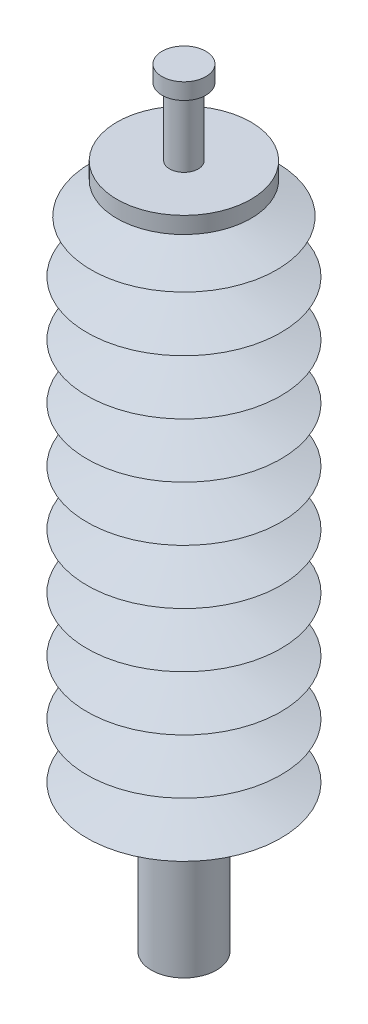
SolidWorks part; units mm, degrees
ref_plane "Alzado" through (0, 0, 0) normal (0, 0, 1) x (1, 0, 0)
ref_plane "Planta" through (0, 0, 0) normal (0, 1, 0) x (1, 0, 0)
ref_plane "Vista lateral" through (0, 0, 0) normal (1, 0, 0) x (0, 0, -1)
sketch "Croquis1" plane through (0, 0, 0) normal (0, 0, 1) x (1, 0, 0)
  line L0 (0, 0) -> (0, 1000)
  line L1 (0, 1000) -> (0, 1050.9393)
  line L2 (21.9878, 1050.9393) -> (102.821, 1050.9393)
  line L3 (102.821, 1050.9393) -> (102.821, 1025.4697)
  line L4 (102.821, 1025.4697) -> (50, 1025.4697)
  line L5 (50, 1025.4697) -> (50, 1000)
  line L6 (50, 1000) -> (142.4367, 976.99)
  line L7 (142.4367, 976.99) -> (50, 921.4009)
  line L8 (50, 921.4009) -> (148.7863, 896.8103)
  line L9 (148.7863, 896.8103) -> (50, 837.4028)
  line L10 (50, 837.4028) -> (148.7863, 812.8122)
  line L11 (148.7863, 812.8122) -> (50, 753.4047)
  line L12 (50, 753.4047) -> (148.7863, 728.8141)
  line L13 (148.7863, 728.8141) -> (50, 669.4065)
  line L14 (50, 669.4065) -> (148.7863, 644.8159)
  line L15 (148.7863, 644.8159) -> (50, 585.4084)
  line L16 (50, 585.4084) -> (148.7863, 560.8178)
  line L17 (148.7863, 560.8178) -> (50, 501.4103)
  line L18 (50, 501.4103) -> (148.7863, 476.8197)
  line L19 (148.7863, 476.8197) -> (50, 417.4122)
  line L20 (50, 417.4122) -> (148.7863, 392.8215)
  line L21 (148.7863, 392.8215) -> (50, 333.414)
  line L22 (50, 333.414) -> (148.7863, 308.8234)
  line L23 (148.7863, 308.8234) -> (50, 249.4159)
  line L24 (50, 249.4159) -> (148.7863, 224.8253)
  line L25 (148.7863, 224.8253) -> (50, 165.4178)
  line L26 (50, 165.4178) -> (50, 0)
  line L27 (50, 0) -> (0, 0)
  line L28 (21.9878, 1050.9393) -> (21.9878, 1154.729)
  line L29 (21.9878, 1154.729) -> (33.6784, 1154.729)
  line L30 (33.6784, 1154.729) -> (33.6784, 1179.5968)
  line L31 (33.6784, 1179.5968) -> (0, 1179.5968)
  line L32 (0, 1179.5968) -> (0, 1050.9393)
  point P31 (0, 0)
  dimension "D1" = 1000
  dimension "D2" = 50
revolve "Revolución1" add sketch "Croquis1" angle 360 about L0
